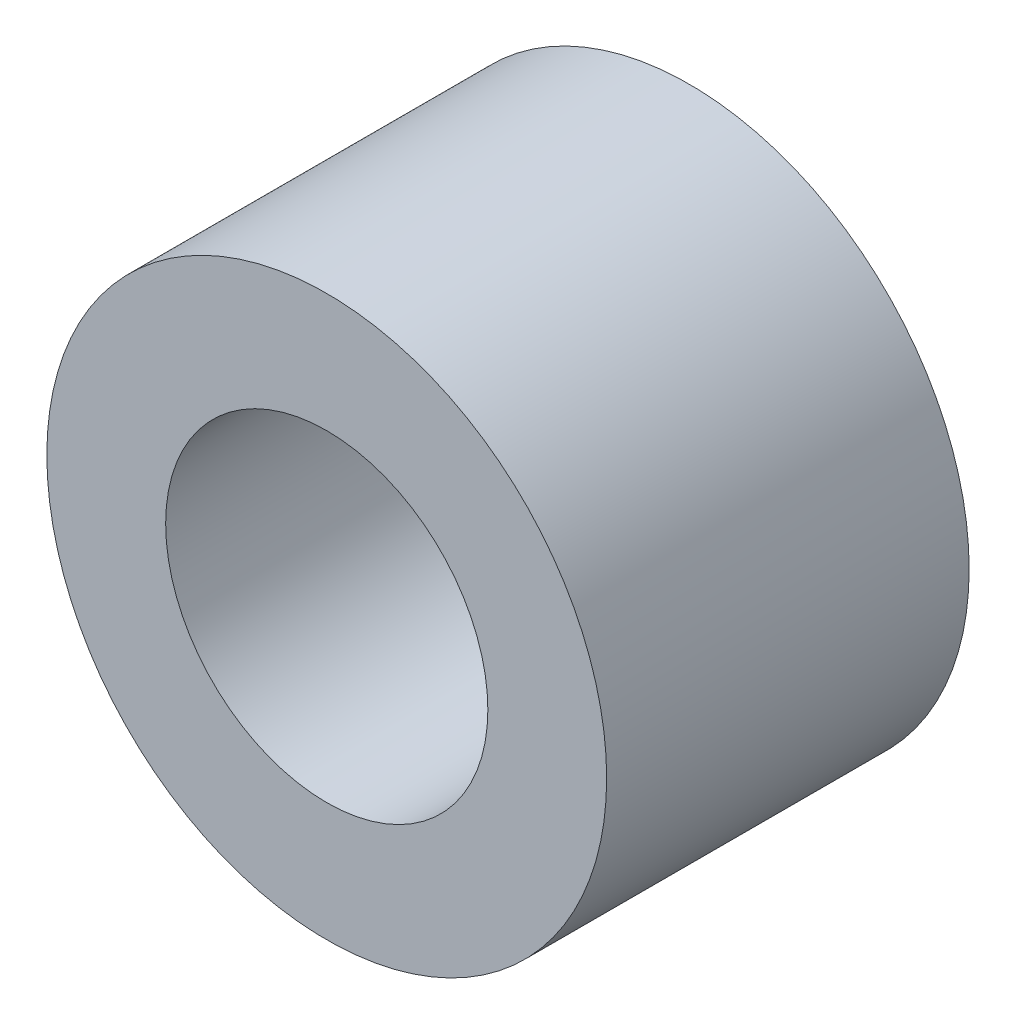
SolidWorks part; units mm, degrees
material "Aluminum Bronze"
ref_plane "Alzado" through (0, 0, 0) normal (0, 0, 1) x (1, 0, 0)
ref_plane "Planta" through (0, 0, 0) normal (0, 1, 0) x (1, 0, 0)
ref_plane "Vista lateral" through (0, 0, 0) normal (1, 0, 0) x (0, 0, -1)
sketch "Sketch1" plane through (0, 0, 0) normal (0, 0, 1) x (1, 0, 0)
  circle A0 centre (0, 0) radius 3.475
  circle A1 centre (0, 0) radius 2
  dimension "D1" = 6.95
  dimension "D2" = 4
extrude "Boss-Extrude1" add sketch "Sketch1" along normal blind 4.5
